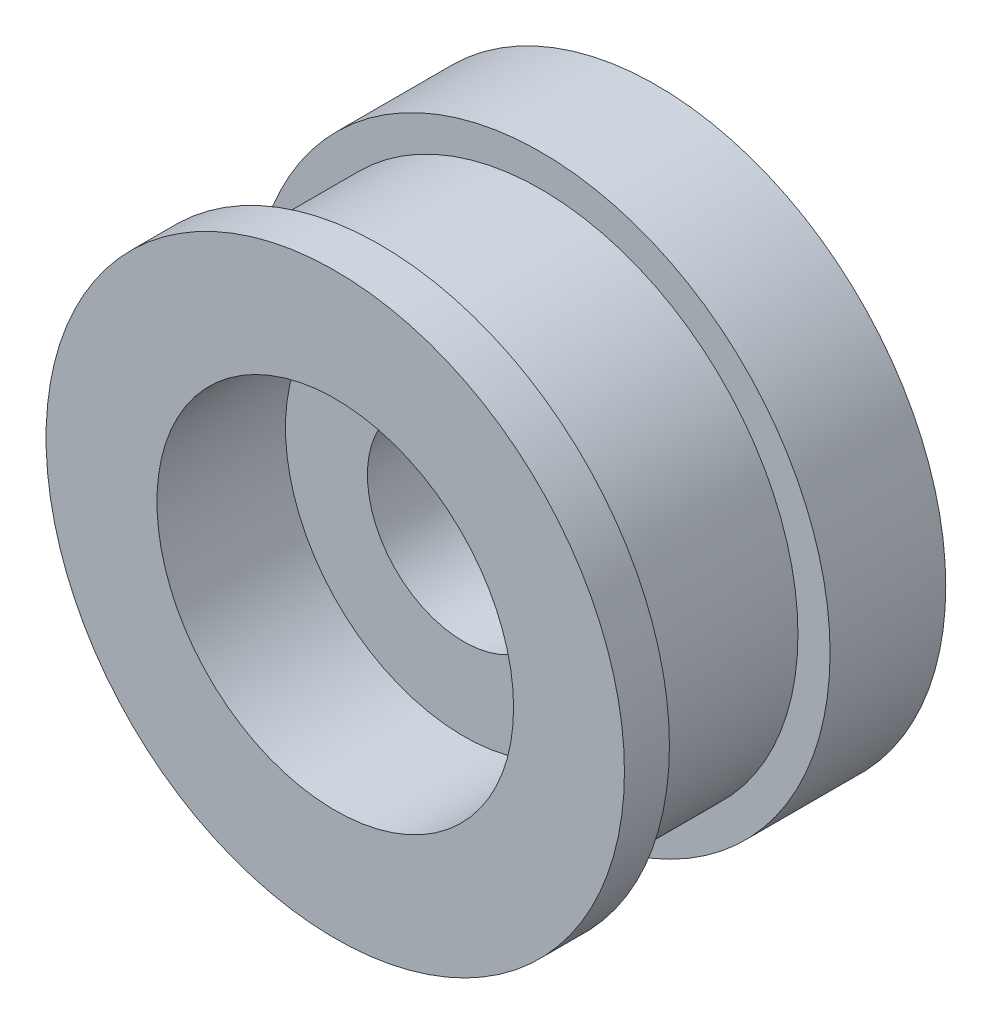
SolidWorks part; units mm, degrees
material "Custom Plastic"
ref_plane "Front Plane" through (0, 0, 0) normal (0, 0, 1) x (1, 0, 0)
ref_plane "Top Plane" through (0, 0, 0) normal (0, 1, 0) x (1, 0, 0)
ref_plane "Right Plane" through (0, 0, 0) normal (1, 0, 0) x (0, 0, -1)
sketch "base" plane through (0, 0, 0) normal (0, 0, 1) x (1, 0, 0)
  circle A0 centre (0, 0) radius 4.5
  dimension "D1" = 9
extrude "body 1" add sketch "base" along normal blind 1.8 contours A0
sketch "thin base" plane through (0, 0, 1.8) normal (0, 0, 1) x (1, 0, 0)
  circle A0 centre (0, 0) radius 4
  dimension "D1" = 8
extrude "body thin" add sketch "thin base" along normal blind 2.5
sketch "base 2" plane through (0, 0, 4.3) normal (0, 0, 1) x (1, 0, 0)
  circle A0 centre (0, 0) radius 4.5
  dimension "D1" = 9
extrude "body 2" add sketch "base 2" along normal blind 0.7
sketch "screw head hole sketch" plane through (0, 0, 5) normal (0, 0, 1) x (1, 0, 0)
  circle A0 centre (0, 0) radius 2.775
  dimension "D1" = 5.55
extrude "screw head hole" cut sketch "screw head hole sketch" against normal blind 2
hole_wizard "Ø3.0 (3) Diameter Hole1" positions "Sketch6" profile "Sketch7" hole size "Ø3.0" standard "ANSI Metric" end condition through all
sketch "Sketch6" plane through (0, 0, 3) normal (0, 0, 1) x (1, 0, 0)
  point P0 (0, 0)
sketch "Sketch7" plane through (0, 0, 3) normal (1, 0, 0) x (0, -1, 0)
  line L0 (0, 0) -> (0, 3)
  line L1 (0, 3) -> (1.5, 3)
  line L2 (1.5, 3) -> (1.5, 0)
  line L5 (1.5, 0) -> (0, 0)
  line L11 (0, -6.35) -> (0, 107.95) construction
  dimension "Thru Hole Dia." = 3
  dimension "Thru Hole Depth" = 3
